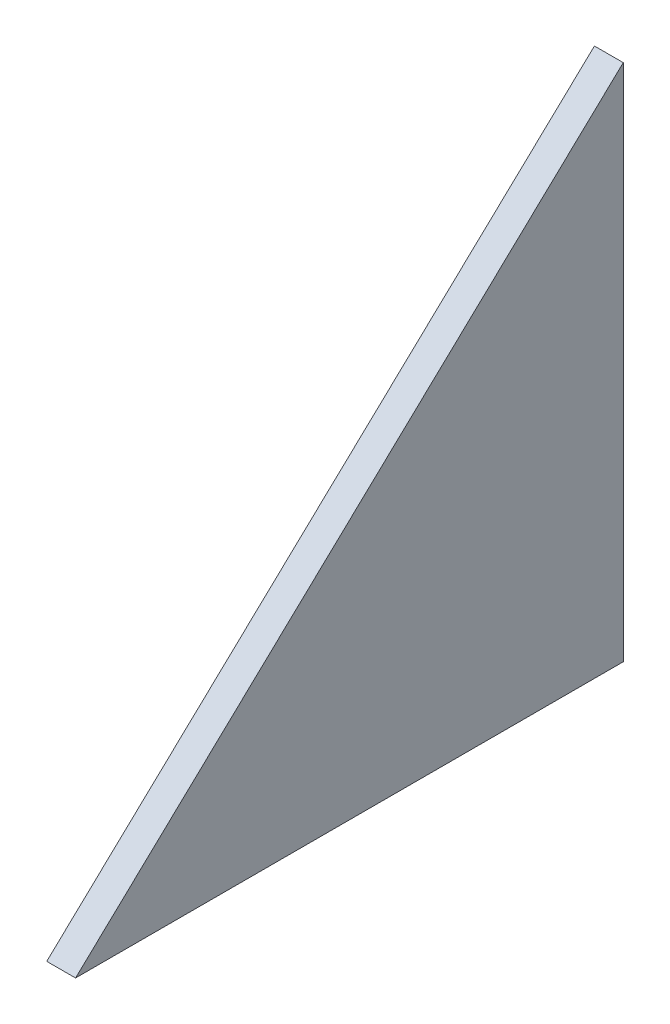
SolidWorks part; units mm, degrees
ref_plane "Front Plane" through (0, 0, 0) normal (0, 0, 1) x (1, 0, 0)
ref_plane "Top Plane" through (0, 0, 0) normal (0, 1, 0) x (1, 0, 0)
ref_plane "Right Plane" through (0, 0, 0) normal (1, 0, 0) x (0, 0, -1)
sketch "Sketch1" plane through (0, 0, 0) normal (1, 0, 0) x (0, 0, -1)
  line L0 (0, 0) -> (95, 0)
  line L1 (0, 0) -> (95, 90)
  line L2 (95, 90) -> (95, 0)
  dimension "D1" = 90
  dimension "D3" = 95
extrude "Boss-Extrude1" add sketch "Sketch1" along normal blind 5
